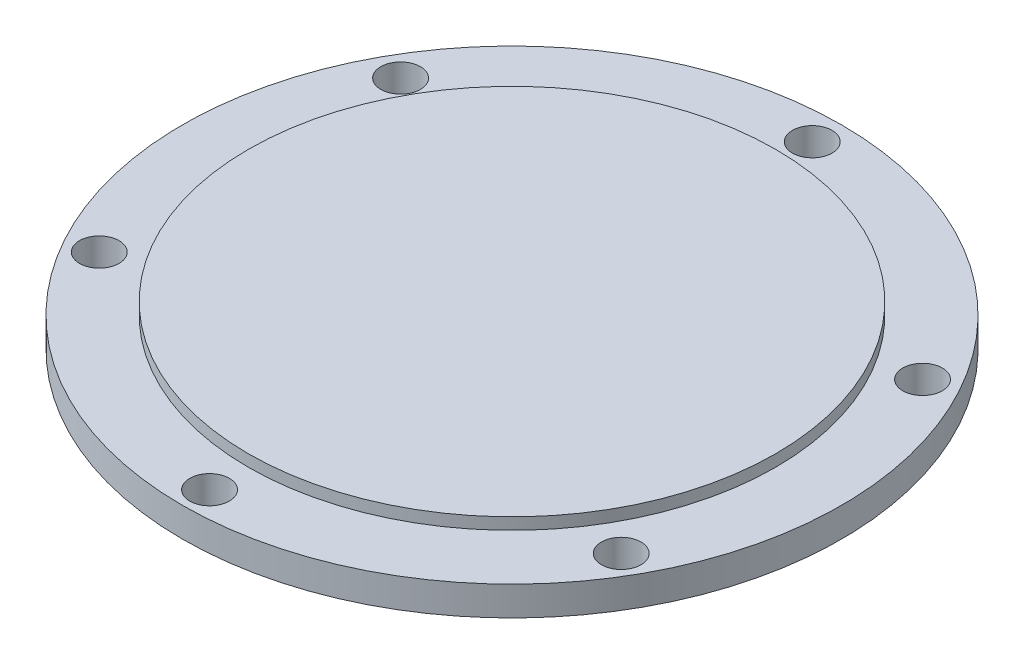
SolidWorks part; units mm, degrees
ref_plane "Alzado" through (0, 0, 0) normal (0, 0, 1) x (1, 0, 0)
ref_plane "Planta" through (0, 0, 0) normal (0, 1, 0) x (1, 0, 0)
ref_plane "Vista lateral" through (0, 0, 0) normal (1, 0, 0) x (0, 0, -1)
sketch "Croquis1" plane through (0, 0, 0) normal (0, 1, 0) x (1, 0, 0)
  circle A0 centre (0, 0) radius 112.5
  dimension "D1" = 225
extrude "Saliente-Extruir1" add sketch "Croquis1" along normal blind 10
sketch "Croquis2" plane through (0, 10, 0) normal (0, 1, 0) x (1, 0, 0)
  circle A0 centre (0, 0) radius 102.5
  dimension "D1" = 205
sketch "Croquis4" plane through (0, 10, 0) normal (0, 1, 0) x (1, 0, 0)
  line L0 (0, 0) -> (0, 135.6598)
hole_wizard "Taladro de margen para M121" positions "Croquis3D2" profile "Croquis5" hole size "M12" standard "Ansi Metric"
sketch3d "Croquis3D2"
  line L0 (0, 10, 0) -> (0, 10, -135.6598) construction
  circle A0 centre (0, 10, 0) radius 102.5 construction
  point P0 (0, 10, -102.5)
  point P4 (0, 112.5, 0)
sketch "Croquis5" plane through (0, 10, -102.5) normal (1, 0, 0) x (0, 0, 1)
  line L0 (0, 0) -> (0, 47.5558)
  line L1 (0, 47.5558) -> (6.75, 43.5)
  line L2 (6.75, 43.5) -> (6.75, 0)
  line L5 (6.75, 0) -> (0, 0)
  line L10 (0, 47.5558) -> (-6.75, 43.5) construction
  line L11 (0, -6.35) -> (0, 107.95) construction
  dimension "Diámetro de taladro" = 13.5
  dimension "Profundidad de taladro" = 43.5
  dimension "Ángulo de perforador" = 118
pattern_circular "MatrizC1" count 6 over 360 about axis through (0, 0, 0.3703) along (0, 1, 0) of "Taladro de margen para M121"
sketch "Croquis6" plane through (0, 10, 0) normal (0, 1, 0) x (1, 0, 0)
  circle A2 centre (0, 0) radius 90
  dimension "D1" = 180
extrude "Saliente-Extruir2" add sketch "Croquis6" along normal blind 4
